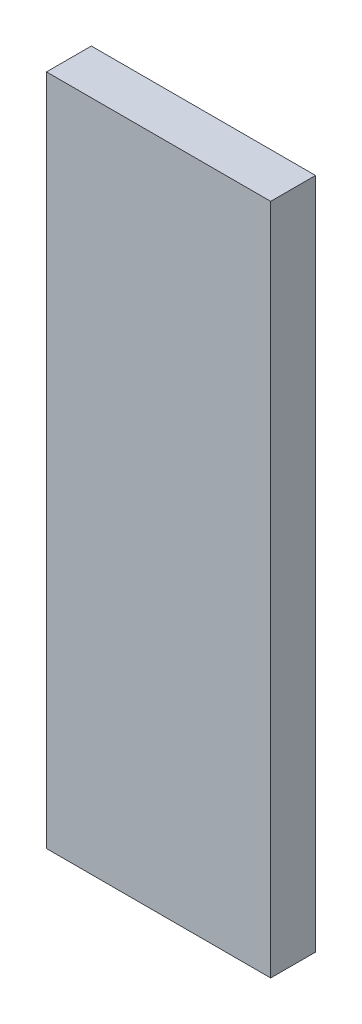
SolidWorks part; units mm, degrees
ref_plane "Alzado" through (0, 0, 0) normal (0, 0, 1) x (1, 0, 0)
ref_plane "Planta" through (0, 0, 0) normal (0, 1, 0) x (1, 0, 0)
ref_plane "Vista lateral" through (0, 0, 0) normal (1, 0, 0) x (0, 0, -1)
sketch "Croquis1" plane through (0, 0, 0) normal (0, 0, 1) x (1, 0, 0)
  line L0 (-53.764, 10.3151) -> (-38.764, 10.3151) construction
  line L1 (-43.764, 10.3151) -> (-38.764, 10.3151)
  line L2 (-43.764, 10.3151) -> (-43.764, 25.3151)
  line L3 (-43.764, 25.3151) -> (-38.764, 25.3151)
  line L4 (-38.764, 10.3151) -> (-38.764, 25.3151)
  line L5 (-43.764, 10.3151) -> (-43.764, 25.3151) construction
extrude "Saliente-Extruir1" add sketch "Croquis1" along normal blind 1
sketch "Croquis2" plane through (0, 0, 0.7) normal (0, 0, 1) x (1, 0, 0)
  line L0 (-1.7519, 12.3697) -> (-1.4019, 11.3697)
  line L1 (-1.4019, 11.3697) -> (2.0981, 11.3697)
  line L2 (2.0981, 11.3697) -> (2.4481, 12.3697)
  line L3 (2.4481, 12.3697) -> (-1.7519, 12.3697)
extrude "Saliente-Extruir2" [suppressed] add sketch "Croquis2" along normal up to surface (0.3 mm away) separate body
